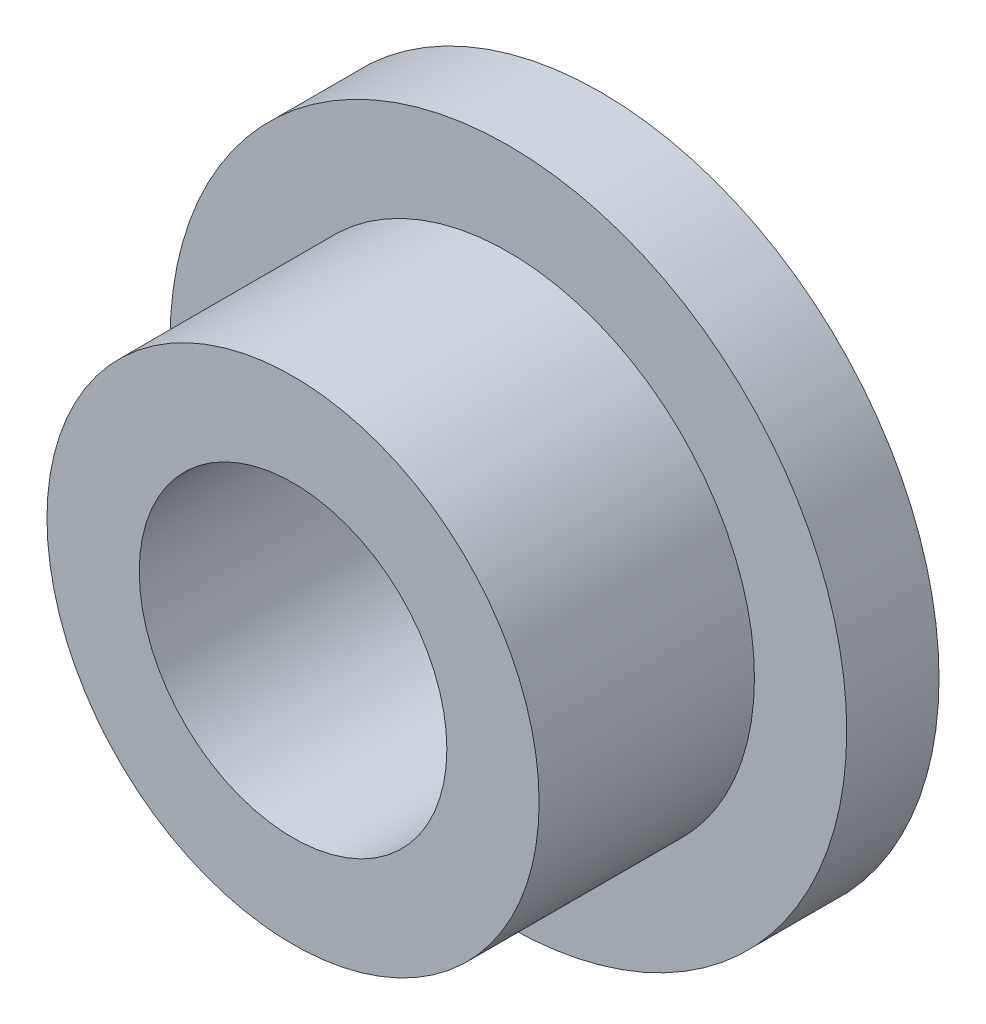
SolidWorks part; units mm, degrees
ref_plane "Front Plane" through (0, 0, 0) normal (0, 0, 1) x (1, 0, 0)
ref_plane "Top Plane" through (0, 0, 0) normal (0, 1, 0) x (1, 0, 0)
ref_plane "Right Plane" through (0, 0, 0) normal (1, 0, 0) x (0, 0, -1)
sketch "Sketch1" plane through (0, 0, 0) normal (0, 0, 1) x (1, 0, 0)
  circle A0 centre (0, 0) radius 11
  dimension "D1" = 22
extrude "Boss-Extrude1" add sketch "Sketch1" along normal blind 3
sketch "Sketch2" plane through (0, 0, 3) normal (0, 0, 1) x (1, 0, 0)
  circle A0 centre (0, 0) radius 8
  dimension "D1" = 16
extrude "Boss-Extrude2" add sketch "Sketch2" along normal blind 7
sketch "Sketch3" plane through (0, 0, 10) normal (0, 0, 1) x (1, 0, 0)
  circle A0 centre (0, 0) radius 5
  dimension "D1" = 10
extrude "Cut-Extrude1" cut sketch "Sketch3" against normal through all
